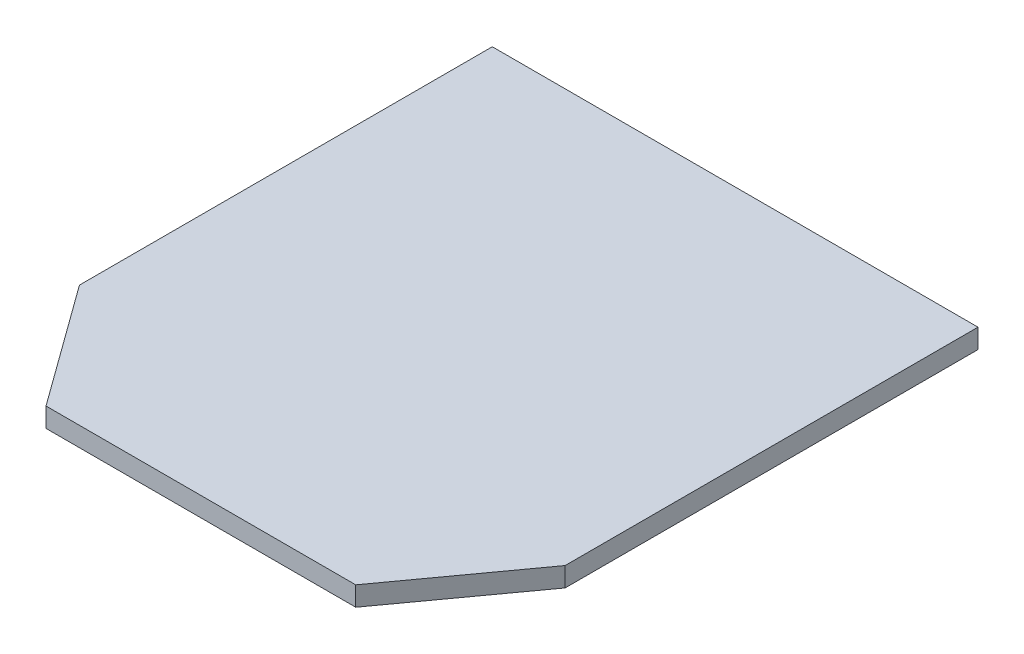
SolidWorks part; units mm, degrees
ref_plane "Front Plane" through (0, 0, 0) normal (0, 0, 1) x (1, 0, 0)
ref_plane "Top Plane" through (0, 0, 0) normal (0, 1, 0) x (1, 0, 0)
ref_plane "Right Plane" through (0, 0, 0) normal (1, 0, 0) x (0, 0, -1)
sketch "Sketch1" plane through (0, 0, 0) normal (0, 1, 0) x (1, 0, 0)
  line L0 (54.8562, 0) -> (-45.1438, 0)
  line L1 (-45.1438, 0) -> (-45.1438, -85)
  line L2 (-45.1438, -85) -> (-27.0288, -110)
  line L4 (54.8562, -85) -> (36.7412, -110)
  line L5 (54.8562, 0) -> (54.8562, -85)
  line L6 (-27.0288, -110) -> (36.7412, -110)
  line L9 (-45.1438, -85) -> (54.8562, -85)
  line L10 (-45.1438, -85) -> (-45.1438, 0)
  line L11 (-45.1438, 0) -> (54.8562, 0)
  line L12 (54.8562, -85) -> (54.8562, 0)
  dimension "D1" = 100
  dimension "D2" = 85
  dimension "D3" = 25
extrude "Boss-Extrude1" add sketch "Sketch1" along normal blind 4 contours L9 L2 L6 L4 | L1 L9 L5 L0
